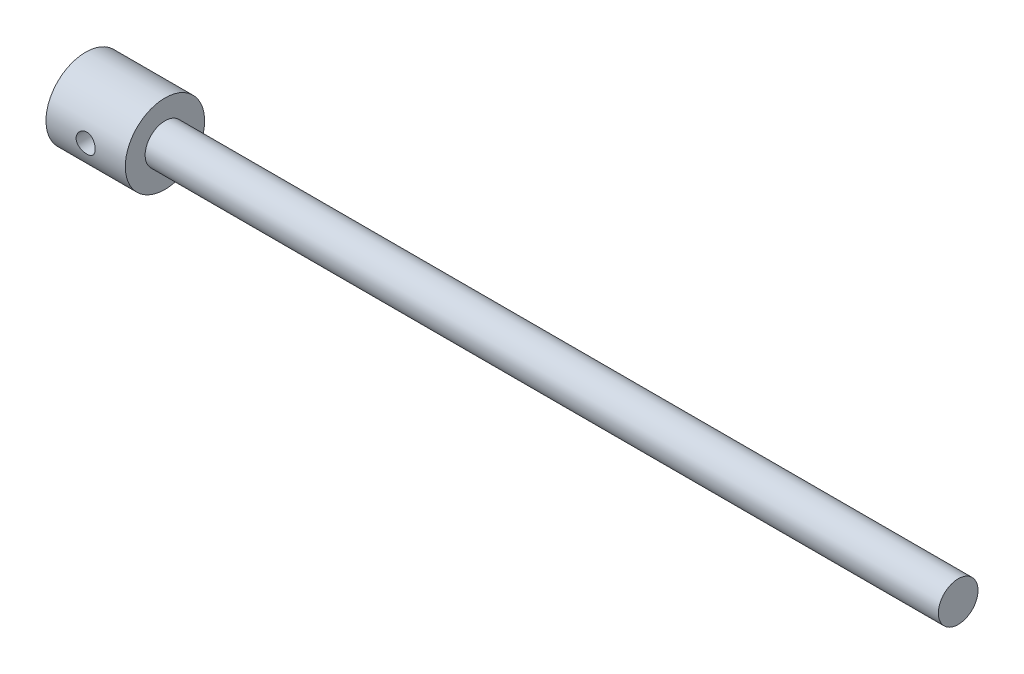
SolidWorks part; units mm, degrees
ref_plane "Front Plane" through (0, 0, 0) normal (0, 0, 1) x (1, 0, 0)
ref_plane "Top Plane" through (0, 0, 0) normal (0, 1, 0) x (1, 0, 0)
ref_plane "Right Plane" through (0, 0, 0) normal (1, 0, 0) x (0, 0, -1)
sketch "Sketch1" plane through (0, 0, 0) normal (0, 0, 1) x (1, 0, 0)
  line L0 (0, 0) -> (0, 25)
  line L1 (0, 25) -> (50, 25)
  line L2 (50, 25) -> (50, 12.5)
  line L3 (50, 12.5) -> (550, 12.5)
  line L4 (550, 12.5) -> (550, 0)
  line L5 (550, 0) -> (0, 0)
  dimension "D1" = 12.5
  dimension "D2" = 25
  dimension "D3" = 50
  dimension "D4" = 500
revolve "Revolve1" add sketch "Sketch1" angle 360 about L5
sketch "Sketch2" plane through (0, 0, 0) normal (0, 0, 1) x (1, 0, 0)
  circle A0 centre (25, 0) radius 6
  dimension "D1" = 12
  dimension "D2" = 25
extrude "Cut-Extrude1" cut sketch "Sketch2" against normal through all both and the other way through all
